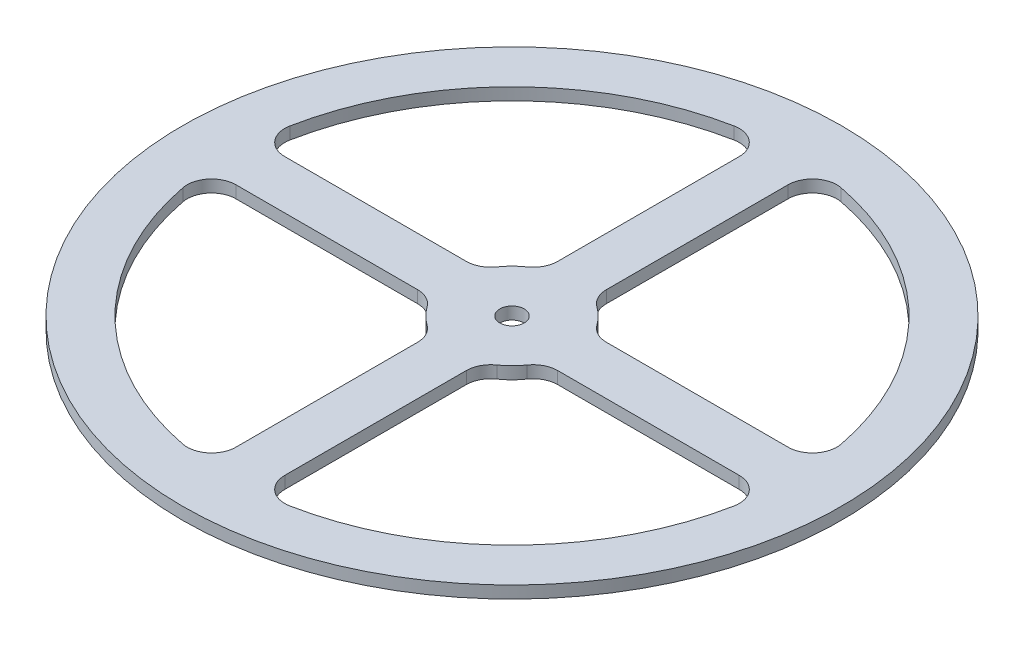
SolidWorks part; units mm, degrees
ref_plane "正面" through (0, 0, 0) normal (0, 0, 1) x (1, 0, 0)
ref_plane "平面" through (0, 0, 0) normal (0, 1, 0) x (1, 0, 0)
ref_plane "右側面" through (0, 0, 0) normal (1, 0, 0) x (0, 0, -1)
sketch "ｽｹｯﾁ1" plane through (0, 0, 0) normal (0, 1, 0) x (1, 0, 0)
  line L0 (-135, 0) -> (0, 0) construction
  line L1 (0, 0) -> (0, 135) construction
  line L2 (-103.0776, 10) -> (-28.7228, 10)
  line L3 (10, 103.0776) -> (10, 28.7228)
  line L4 (103.0776, 10) -> (28.7228, 10)
  line L5 (-10, 103.0776) -> (-10, 28.7228)
  line L6 (103.0776, -10) -> (28.7228, -10)
  line L7 (10, -103.0776) -> (10, -28.7228)
  line L8 (-10, -103.0776) -> (-10, -28.7228)
  line L9 (-103.0776, -10) -> (-28.7228, -10)
  circle A0 centre (0, 0) radius 135
  circle A1 centre (0, 0) radius 5
  arc A2 (-21.9048, 112.8946) -> (-112.8946, 21.9048) centre (0, 0) ccw
  arc A3 (-14.2857, 20.5163) -> (-20.5163, 14.2857) centre (0, 0) ccw
  circle A4 centre (0, 0) radius 115 construction
  circle A5 centre (0, 0) radius 25 construction
  arc A6 (-21.9048, 112.8946) -> (-10, 103.0776) centre (-20, 103.0776) cw
  arc A7 (-10, 28.7228) -> (-14.2857, 20.5163) centre (-20, 28.7228) cw
  arc A8 (-28.7228, 10) -> (-20.5163, 14.2857) centre (-28.7228, 20) ccw
  arc A9 (-103.0776, 10) -> (-112.8946, 21.9048) centre (-103.0776, 20) cw
  arc A10 (20.5163, 14.2857) -> (14.2857, 20.5163) centre (0, 0) ccw
  arc A11 (10, 28.7228) -> (14.2857, 20.5163) centre (20, 28.7228) ccw
  arc A12 (28.7228, 10) -> (20.5163, 14.2857) centre (28.7228, 20) cw
  arc A13 (10, 103.0776) -> (21.9048, 112.8946) centre (20, 103.0776) cw
  arc A14 (112.8946, 21.9048) -> (21.9048, 112.8946) centre (0, 0) ccw
  arc A15 (112.8946, 21.9048) -> (103.0776, 10) centre (103.0776, 20) cw
  arc A16 (14.2857, -20.5163) -> (20.5163, -14.2857) centre (0, 0) ccw
  arc A17 (28.7228, -10) -> (20.5163, -14.2857) centre (28.7228, -20) ccw
  arc A18 (10, -28.7228) -> (14.2857, -20.5163) centre (20, -28.7228) cw
  arc A19 (103.0776, -10) -> (112.8946, -21.9048) centre (103.0776, -20) cw
  arc A20 (21.9048, -112.8946) -> (112.8946, -21.9048) centre (0, 0) ccw
  arc A21 (21.9048, -112.8946) -> (10, -103.0776) centre (20, -103.0776) cw
  arc A22 (-20.5163, -14.2857) -> (-14.2857, -20.5163) centre (0, 0) ccw
  arc A23 (-10, -28.7228) -> (-14.2857, -20.5163) centre (-20, -28.7228) ccw
  arc A24 (-28.7228, -10) -> (-20.5163, -14.2857) centre (-28.7228, -20) cw
  arc A25 (-10, -103.0776) -> (-21.9048, -112.8946) centre (-20, -103.0776) cw
  arc A26 (-112.8946, -21.9048) -> (-21.9048, -112.8946) centre (0, 0) ccw
  arc A27 (-112.8946, -21.9048) -> (-103.0776, -10) centre (-103.0776, -20) cw
  dimension "D1" = 10
  dimension "D2" = 270
  dimension "D7" = 10
  dimension "D3" = 20
  dimension "D5" = 10
  dimension "D6" = 10
  dimension "D4" = 20
  dimension "D8" = 4
extrude "ﾎﾞｽ - 押し出し1" add sketch "ｽｹｯﾁ1" along normal blind 5
